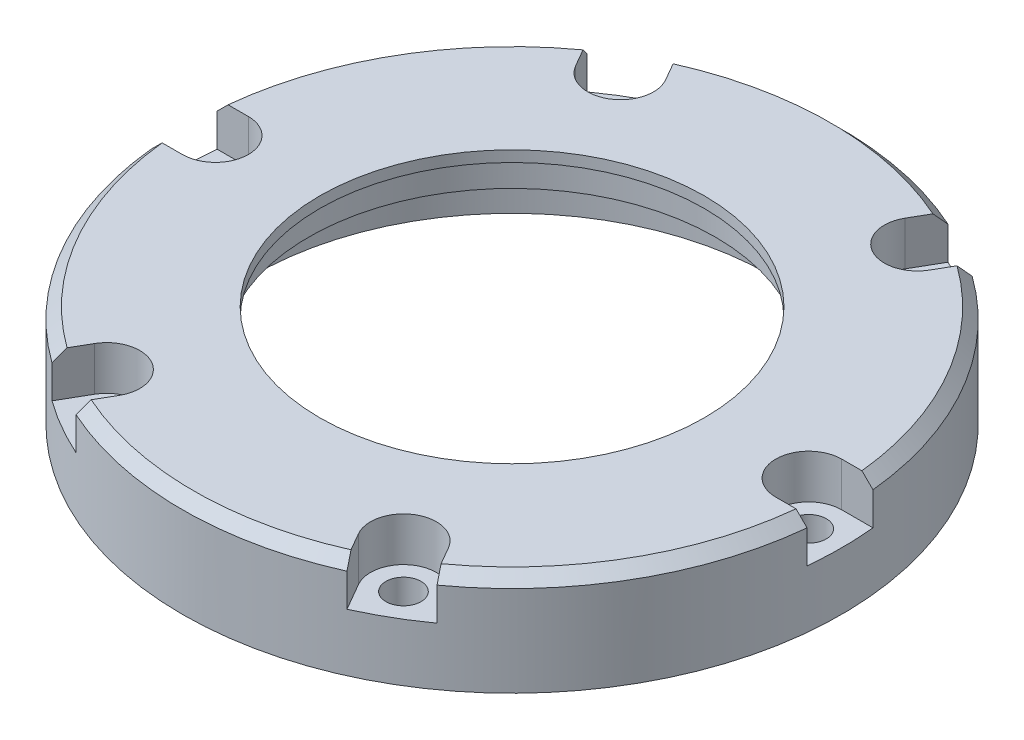
SolidWorks part; units mm, degrees
material "Like ABS"
ref_plane "Front Plane" through (0, 0, 0) normal (0, 0, 1) x (1, 0, 0)
ref_plane "Top Plane" through (0, 0, 0) normal (0, 1, 0) x (1, 0, 0)
ref_plane "Right Plane" through (0, 0, 0) normal (1, 0, 0) x (0, 0, -1)
sketch "Sketch1" plane through (0, 0, 0) normal (0, 1, 0) x (1, 0, 0)
  circle A0 centre (0, 0) radius 30
  circle A1 centre (0, 0) radius 17.5
  dimension "D1" = 60
  dimension "D2" = 35
extrude "Boss-Extrude1" add sketch "Sketch1" along normal blind 9.25
sketch "Sketch2" plane through (0, 9.25, 0) normal (0, 1, 0) x (1, 0, 0)
  line L0 (0, 0) -> (-27, 0) construction
  circle A0 centre (-27, 0) radius 1.6
  dimension "D2" = 3.2
  dimension "D1" = 27
extrude "Cut-Extrude1" cut sketch "Sketch2" against normal up to surface (9.25 mm away) up to face at (0, 0, 30)
sketch "Sketch3" plane through (0, 9.25, 0) normal (0, 1, 0) x (1, 0, 0)
  line L1 (-27, 3) -> (-31.5102, 3)
  line L3 (-27, -3) -> (-31.5102, -3)
  line L4 (-31.5102, 3) -> (-31.5102, -3)
  arc A0 (-27, -3) -> (-27, 3) centre (-27, 0) ccw
  dimension "D1" = 6
extrude "Cut-Extrude2" cut sketch "Sketch3" against normal blind 4
sketch "Sketch4" plane through (0, 0, 0) normal (0, -1, 0) x (1, 0, 0)
  circle A0 centre (0, 0) radius 23.5
  dimension "D1" = 47
extrude "Cut-Extrude3" cut sketch "Sketch4" against normal blind 5.5
sketch "Sketch5" plane through (0, 0, 0) normal (0, -1, 0) x (1, 0, 0)
  circle A0 centre (0, 0) radius 18.5
  dimension "D1" = 37
extrude "Cut-Extrude4" cut sketch "Sketch5" against normal blind 8.25
pattern_circular "CirPattern1" count 6 over 360 about axis through (0, 0, 0) along (0, 1, 0) of "Cut-Extrude1", "Cut-Extrude2"
chamfer "Chamfer1" distance 1 angle 45 6 edges at (25.9808, 9.25, -15) (0, 9.25, -30) (-25.9808, 9.25, -15) (-25.9808, 9.25, 15) (0, 9.25, 30) (25.9808, 9.25, 15)
